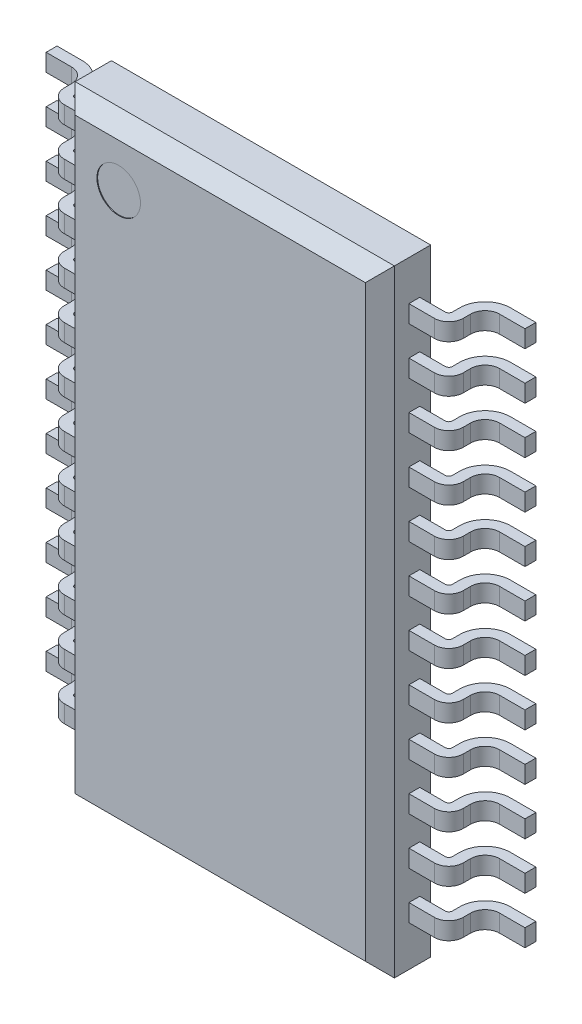
SolidWorks part; units mm, degrees
ref_plane "前视基准面" through (0, 0, 0) normal (0, 0, 1) x (1, 0, 0)
ref_plane "上视基准面" through (0, 0, 0) normal (0, 1, 0) x (1, 0, 0)
ref_plane "右视基准面" through (0, 0, 0) normal (1, 0, 0) x (0, 0, -1)
ref_plane "基准面1" through (0, 0, 0.15) normal (0, 0, 1) x (1, 0, 0)
sketch "草图1" plane through (0, 0, 0.15) normal (0, 0, 1) x (1, 0, 0)
  line L1 (-2.2, 4.9) -> (2.2, 4.9)
  line L2 (-2.2, 4.9) -> (-2.2, -3.6)
  line L3 (-2.2, -3.6) -> (2.2, -3.6)
  line L4 (2.2, 4.9) -> (2.2, -3.6)
  dimension "D1" = 4.4
  dimension "D2" = 8.5
  dimension "D3" = 4.9
  dimension "D4" = 2.2
extrude "拉伸1" add sketch "草图1" along normal blind 0.9
chamfer "倒角1" distance 0.2 angle 45 8 edges at (0, 4.9, 0.15) (-2.2, 0.65, 0.15) (0, -3.6, 0.15) (2.2, 0.65, 0.15) (2.2, 0.65, 1.05) (0, -3.6, 1.05) (-2.2, 0.65, 1.05) (0, 4.9, 1.05)
ref_plane "基准面2" through (0, 0.33, 0) normal (0, 1, 0) x (-1, 0, 0)
sketch "草图5" plane through (0, 0.33, 0) normal (0, 1, 0) x (1, 0, 0)
  line L0 (-2.2, -0.65) -> (-2.55, -0.65)
  line L1 (-2.2, -0.85) -> (-2.2, -0.35) construction
  line L2 (-2.75, -0.45) -> (-2.75, -0.35)
  line L3 (-2.95, -0.15) -> (-3.3, -0.15)
  line L5 (-2, -1.05) -> (2, -1.05) construction
  arc A0 (-2.75, -0.45) -> (-2.55, -0.65) centre (-2.55, -0.45) ccw
  arc A1 (-2.95, -0.15) -> (-2.75, -0.35) centre (-2.95, -0.35) cw
  point P13 (-2.75, -0.15)
  dimension "D5" = 0.2
  dimension "D1" = 3.3
  dimension "D2" = 0.15
  dimension "D3" = 0.4
  dimension "D4" = 0.55
sketch "草图6" plane through (-2.2, 0, 0) normal (1, 0, 0) x (0, 0, -1)
  line L2 (-0.5, 0.45) -> (-0.65, 0.45)
  line L3 (-0.5, 0.45) -> (-0.5, 0.21)
  line L4 (-0.5, 0.21) -> (-0.65, 0.21)
  line L5 (-0.65, 0.45) -> (-0.65, 0.21)
  dimension "D1" = 0.15
  dimension "D2" = 0.24
sweep "扫描1" add profiles "草图6" path "草图5"
pattern_linear "阵列(线性)1" count 6 spacing 0.65 along (0, -1, 0) count 7 spacing 0.65 along (0, 1, 0) of "扫描1"
mirror "镜向1" about plane through (0, 0, 0) normal (1, 0, 0) of "阵列(线性)1", "扫描1"
sketch "草图7" plane through (0, 0, 1.05) normal (0, 0, 1) x (1, 0, 0)
  line L0 (2.2, 4.9) -> (-2.2, 4.9) construction
  line L1 (-2.2, 4.9) -> (-2.2, -3.6) construction
  circle A0 centre (-1.4, 4.1) radius 0.3
  dimension "D1" = 0.6
  dimension "D2" = 0.8
  dimension "D3" = 0.8
extrude "切除-拉伸1" cut sketch "草图7" against normal blind 0.01
